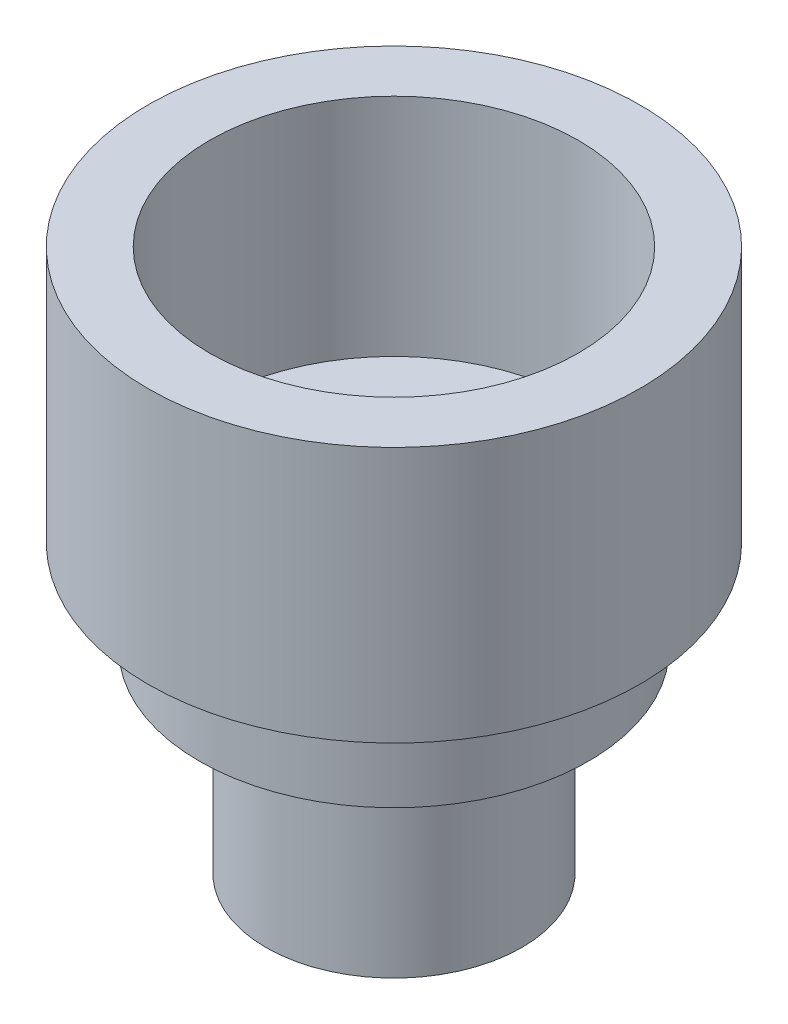
SolidWorks part; units mm, degrees
material "ABS"
ref_plane "Front Plane" through (0, 0, 0) normal (0, 0, 1) x (1, 0, 0)
ref_plane "Top Plane" through (0, 0, 0) normal (0, 1, 0) x (1, 0, 0)
ref_plane "Right Plane" through (0, 0, 0) normal (1, 0, 0) x (0, 0, -1)
sketch "Sketch1" plane through (0, 0, 0) normal (0, 1, 0) x (1, 0, 0)
  circle A0 centre (0, 0) radius 1.25
  dimension "D1" = 2.5
extrude "Boss-Extrude1" add sketch "Sketch1" along normal blind 1.9
sketch "Sketch2" plane through (0, 1.9, 0) normal (0, 1, 0) x (1, 0, 0)
  circle A0 centre (0, 0) radius 1.9
  dimension "D1" = 3.8
extrude "Boss-Extrude2" add sketch "Sketch2" along normal blind 0.9
ref_plane "Plane1" through (0, 5.3, 0) normal (0, 1, 0) x (1, 0, 0)
sketch "Sketch4" plane through (0, 5.3, 0) normal (0, 1, 0) x (1, 0, 0)
  circle A0 centre (0, 0) radius 2.4
  dimension "D1" = 4.8
extrude "Boss-Extrude4" add sketch "Sketch4" against normal up to surface (2.5 mm away) up to face at (0, 2.8, 1.9)
sketch "Sketch6" plane through (0, 5.3, 0) normal (0, 1, 0) x (1, 0, 0)
  circle A0 centre (0, 0) radius 1.8
  circle A1 centre (0, 0) radius 2.4 construction
  dimension "D1" = 0.6
extrude "Cut-Extrude2" cut sketch "Sketch6" against normal blind 2.2
sketch "Sketch5" plane through (0, 3.1, 0) normal (0, 1, 0) x (1, 0, 0)
  circle A0 centre (0, 0) radius 1
  dimension "D1" = 2
extrude "Cut-Extrude1" cut sketch "Sketch5" against normal offset from surface (2.9 mm away) 0.2 up to face at (0, 0, 1.25)
